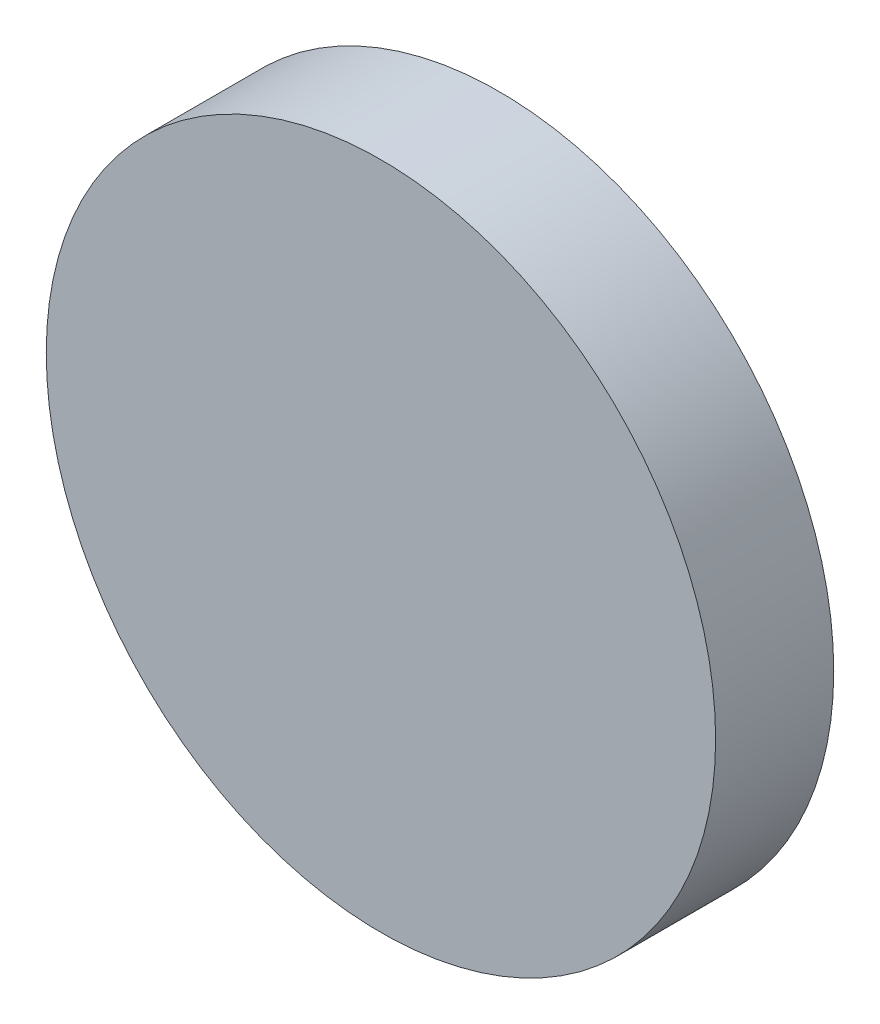
SolidWorks part; units mm, degrees
ref_plane "Front Plane" through (0, 0, 0) normal (0, 0, 1) x (1, 0, 0)
ref_plane "Top Plane" through (0, 0, 0) normal (0, 1, 0) x (1, 0, 0)
ref_plane "Right Plane" through (0, 0, 0) normal (1, 0, 0) x (0, 0, -1)
sketch "Sketch1" plane through (0, 0, 0) normal (0, 0, 1) x (1, 0, 0)
  circle A0 centre (0, 0) radius 32
  circle A1 centre (0, 0) radius 34
  dimension "D1" = 64
  dimension "D2" = 2
extrude "Boss-Extrude1" add sketch "Sketch1" along normal blind 12
ref_plane "Plane1" through (0, 0, 12) normal (0, 0, 1) x (1, 0, 0)
sketch "Sketch2" plane through (0, 0, 12) normal (0, 0, 1) x (1, 0, 0)
  circle A0 centre (0, 0) radius 34
extrude "Boss-Extrude2" add sketch "Sketch2" against normal blind 2
sketch "Sketch3" plane through (0, 0, 10) normal (0, 0, -1) x (-1, 0, 0)
  circle A0 centre (0, 0) radius 8.5
  circle A1 centre (0, 0) radius 10
  dimension "D1" = 17
  dimension "D2" = 1.5
extrude "Boss-Extrude3" add sketch "Sketch3" along normal blind 7
